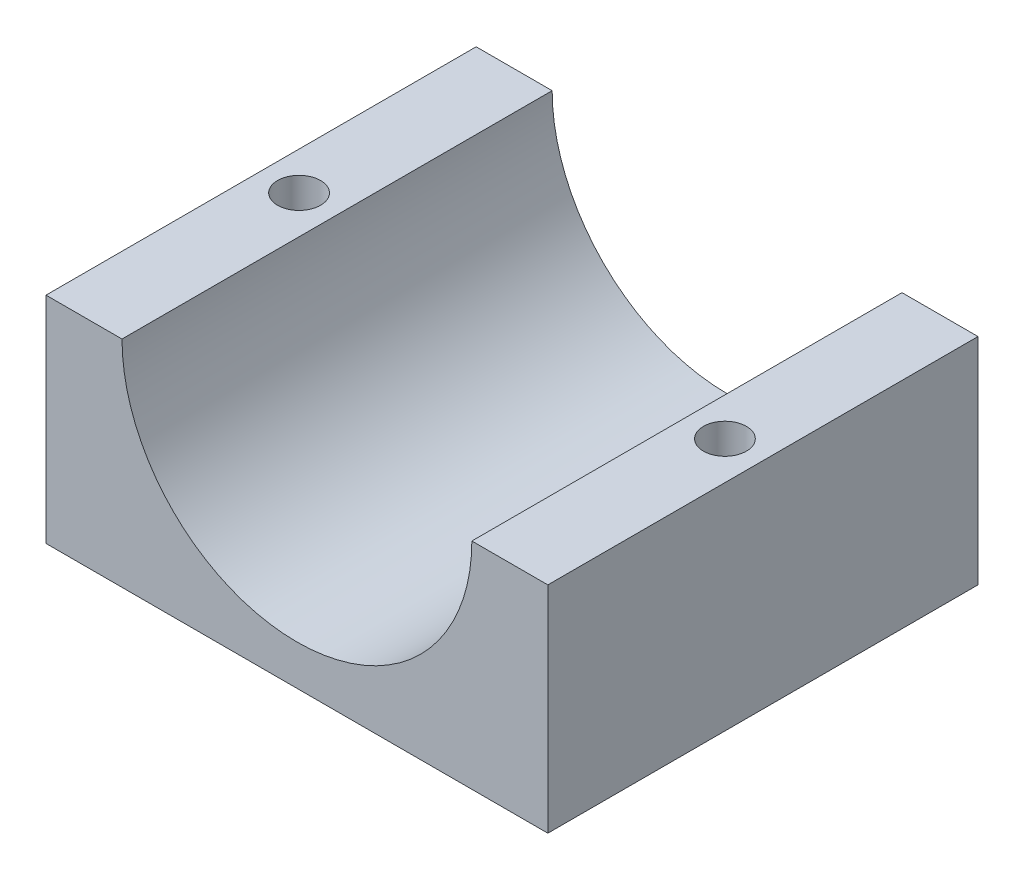
SolidWorks part; units mm, degrees
ref_plane "Front Plane" through (0, 0, 0) normal (0, 0, 1) x (1, 0, 0)
ref_plane "Top Plane" through (0, 0, 0) normal (0, 1, 0) x (1, 0, 0)
ref_plane "Right Plane" through (0, 0, 0) normal (1, 0, 0) x (0, 0, -1)
sketch "Sketch1" plane through (0, 0, 0) normal (0, 1, 0) x (1, 0, 0)
  line L1 (-17.5, 15) -> (17.5, 15)
  line L2 (-17.5, 15) -> (-17.5, -15)
  line L3 (-17.5, -15) -> (17.5, -15)
  line L4 (17.5, 15) -> (17.5, -15)
  point P4 (-17.5, 0)
  point P6 (0, -15)
  dimension "D1" = 35
  dimension "D2" = 30
extrude "Boss-Extrude1" add sketch "Sketch1" along normal blind 15
sketch "Sketch2" plane through (0, 0, 15) normal (0, 0, 1) x (1, 0, 0)
  circle A0 centre (0, 15) radius 12.2
  dimension "D1" = 24.4
  dimension "D2" = 15
extrude "Cut-Extrude1" cut sketch "Sketch2" against normal up to next
sketch "Sketch4" plane through (0, 15, 0) normal (0, 1, 0) x (1, 0, 0)
  line L0 (-17.5, -15) -> (-12.2, -15) construction
  line L1 (-17.5, 15) -> (-17.5, -15) construction
  point P0 (-14.85, 0)
  point P4 (-14.85, -15)
  point P8 (-17.5, 0)
sketch "Sketch5" plane through (0, 15, 0) normal (0, 1, 0) x (1, 0, 0)
  line L0 (17.5, -15) -> (17.5, 15) construction
  line L1 (12.2, -15) -> (17.5, -15) construction
  point P0 (14.85, 0)
  point P4 (17.5, 0)
  point P7 (14.85, -15)
hole_wizard "Ø3.0mm Dowel Hole1" positions "3DSketch2" profile "Sketch6" hole size "Ø3.0" standard "ANSI Metric" end condition through all
sketch3d "3DSketch2"
  point P0 (-14.85, 15, 0)
  point P3 (14.85, 15, 0)
sketch "Sketch6" plane through (-14.85, 15, 0) normal (1, 0, 0) x (0, 0, 1)
  line L0 (0, 0) -> (0, 15)
  line L1 (0, 15) -> (1.5, 15)
  line L2 (1.5, 15) -> (1.5, 0)
  line L5 (1.5, 0) -> (0, 0)
  line L11 (0, -6.35) -> (0, 107.95) construction
  dimension "Thru Hole Dia." = 3
  dimension "Thru Hole Depth" = 15
